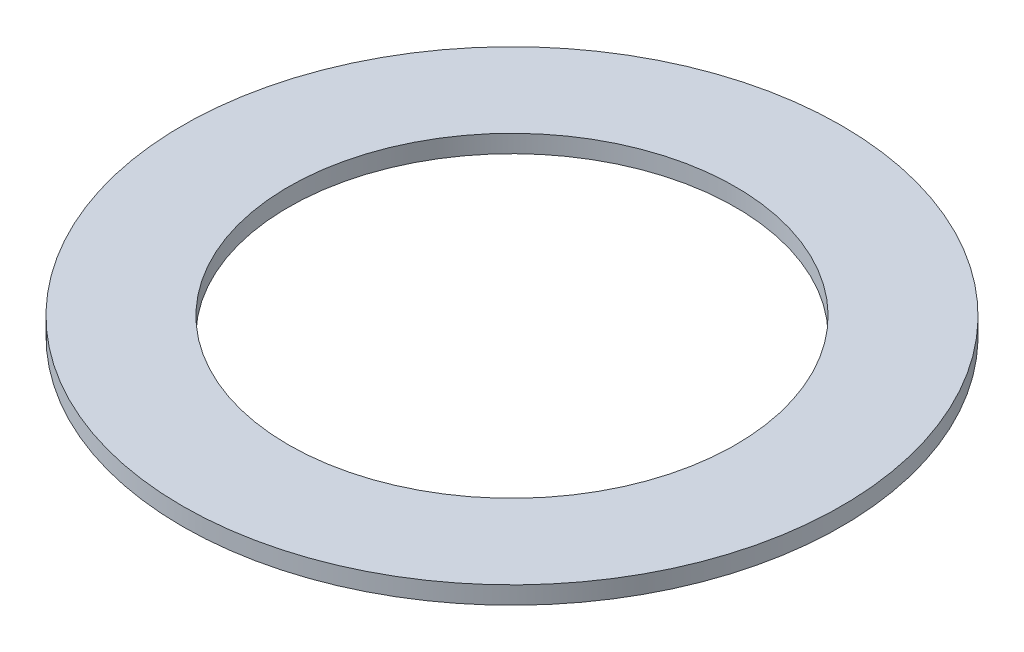
SolidWorks part; units mm, degrees
material "6061-T6 (SS)"
ref_plane "Front Plane" through (0, 0, 0) normal (0, 0, 1) x (1, 0, 0)
ref_plane "Top Plane" through (0, 0, 0) normal (0, 1, 0) x (1, 0, 0)
ref_plane "Right Plane" through (0, 0, 0) normal (1, 0, 0) x (0, 0, -1)
sketch "Sketch1" plane through (0, 0, 0) normal (0, 1, 0) x (1, 0, 0)
  circle A0 centre (0, 0) radius 3.2131
  circle A1 centre (0, 0) radius 4.7371
  dimension "D1" = 6.4262
  dimension "D2" = 9.4742
extrude "Boss-Extrude1" add sketch "Sketch1" along normal mid plane 0.254
